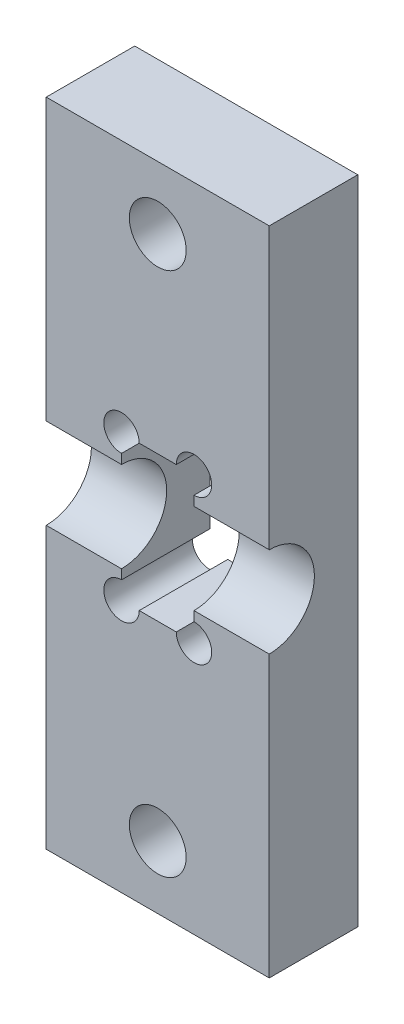
SolidWorks part; units mm, degrees
ref_plane "Top Plane" through (0, 0, 0) normal (0, 0, 1) x (1, 0, 0)
ref_plane "Front Plane" through (0, 0, 0) normal (0, 1, 0) x (1, 0, 0)
ref_plane "Right Plane" through (0, 0, 0) normal (1, 0, 0) x (0, 0, -1)
sketch "Sketch1" plane through (0, 0, 0) normal (0, 0, 1) x (1, 0, 0)
  line L0 (13.25, 24.2975) -> (13.25, 34.1225)
  line L1 (0, 0) -> (20, 0)
  line L2 (0, 0) -> (0, 58.42)
  line L3 (0, 58.42) -> (20, 58.42)
  line L4 (20, 0) -> (20, 58.42)
  line L5 (11.6625, 35.71) -> (8.3375, 35.71)
  line L6 (6.75, 34.1225) -> (6.75, 24.2975)
  line L7 (8.3375, 22.71) -> (11.6625, 22.71)
  line L8 (10, 52.78) -> (10, 5.64) construction
  circle A0 centre (10, 52.78) radius 2.55
  circle A1 centre (10, 5.64) radius 2.55
  arc A4 (13.25, 24.2975) -> (11.6625, 22.71) centre (13.25, 22.71) cw
  arc A5 (8.3375, 22.71) -> (6.75, 24.2975) centre (6.75, 22.71) cw
  arc A6 (6.75, 34.1225) -> (8.3375, 35.71) centre (6.75, 35.71) cw
  arc A7 (13.25, 34.1225) -> (11.6625, 35.71) centre (13.25, 35.71) ccw
  point P22 (13.25, 29.21)
  point P23 (20, 29.21)
  point P24 (10, 35.71)
  point P25 (10, 58.42)
  point P26 (10, 29.21)
  dimension "D1" = 13
  dimension "D3" = 1.5875
  dimension "D4" = 5.1
  dimension "D2" = 6.5
  dimension "D5" = 58.42
  dimension "D6" = 47.14
  dimension "D7" = 20
extrude "Boss-Extrude1" add sketch "Sketch1" along normal blind 7.9375
sketch "Sketch2" plane through (20, 0, 0) normal (1, 0, 0) x (0, 0, -1)
  line L0 (-7.9375, 0) -> (-7.9375, 58.42) construction
  line L1 (-7.9375, 33.26) -> (-7.9375, 25.16)
  arc A0 (-7.9375, 25.16) -> (-7.9375, 33.26) centre (-7.9375, 29.21) ccw
  dimension "D1" = 4.05
extrude "Cut-Extrude1" cut sketch "Sketch2" against normal through all
